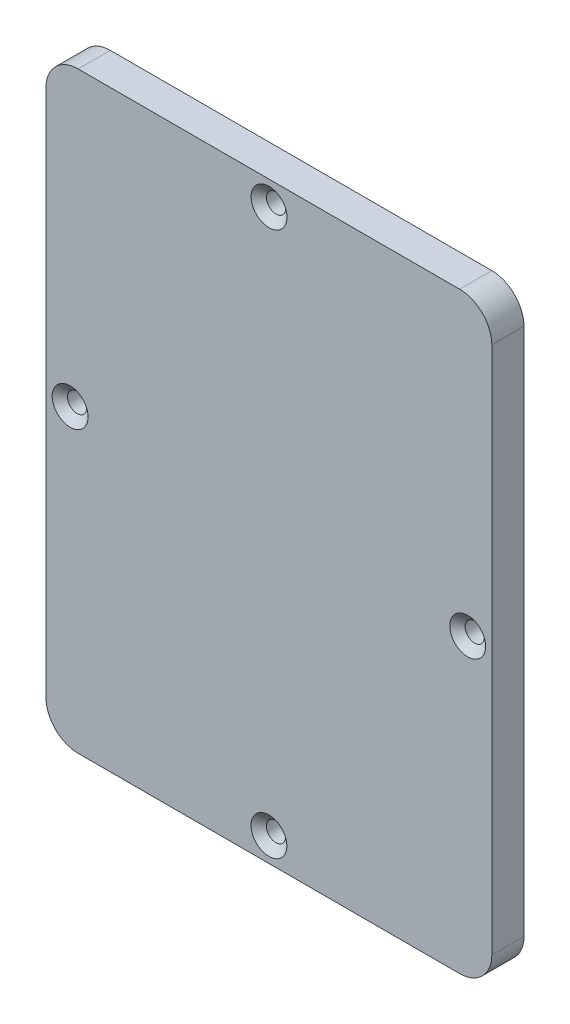
SolidWorks part; units mm, degrees
ref_plane "Front Plane" through (0, 0, 0) normal (0, 0, 1) x (1, 0, 0)
ref_plane "Top Plane" through (0, 0, 0) normal (0, 1, 0) x (1, 0, 0)
ref_plane "Right Plane" through (0, 0, 0) normal (1, 0, 0) x (0, 0, -1)
sketch "Sketch1" plane through (0, 0, 0) normal (0, 0, 1) x (1, 0, 0)
  line L4 (37.65, 117) -> (37.65, 0) construction
  line L5 (37.65, 0) -> (-6.35, 58.5) construction
  line L6 (-6.35, 58.5) -> (81.65, 58.5) construction
  line L8 (0, 0) -> (75.3, 0)
  line L9 (81.65, 6.35) -> (81.65, 110.65)
  line L10 (75.3, 117) -> (0, 117)
  line L11 (-6.35, 110.65) -> (-6.35, 6.35)
  arc A8 (-6.35, 6.35) -> (0, 0) centre (0, 6.35) ccw
  arc A9 (75.3, 0) -> (81.65, 6.35) centre (75.3, 6.35) ccw
  arc A10 (81.65, 110.65) -> (75.3, 117) centre (75.3, 110.65) ccw
  arc A11 (0, 117) -> (-6.35, 110.65) centre (0, 110.65) ccw
  circle A12 centre (37.65, 4.7625) radius 1.5875
  circle A13 centre (76.8875, 58.5) radius 1.5875
  circle A14 centre (37.6738, 112.2375) radius 1.5875
  circle A15 centre (-1.5875, 58.5) radius 1.5875
  point P16 (0, 0)
  point P26 (0, 0)
  point P27 (0, 0)
  point P28 (0, 0)
  dimension "D7" = 6.35
  dimension "D1" = 4.7625
  dimension "D2" = 4.7625
  dimension "D3" = 4.7625
  dimension "D4" = 4.7625
  dimension "D5" = 117
  dimension "D6" = 88
extrude "Boss-Extrude1" add sketch "Sketch1" along normal blind 6.35
hole_wizard "CSK for #6 Flat Head Machine Screw (100)1" positions "Sketch2" profile "Sketch3" countersink size "#6" standard "ANSI Inch" end condition through all
sketch "Sketch2" plane through (0, 0, 6.35) normal (0, 0, 1) x (1, 0, 0)
  point P0 (-1.5875, 58.5)
  point P3 (37.6738, 112.2375)
  point P6 (76.8875, 58.5)
  point P9 (37.65, 4.7625)
sketch "Sketch3" plane through (-1.5875, 58.5, 6.35) normal (1, 0, 0) x (0, -1, 0)
  line L0 (0, 0) -> (0, 6.35)
  line L1 (0, 6.35) -> (1.8986, 6.35)
  line L2 (1.8986, 6.35) -> (1.8986, 1.38)
  line L3 (1.8986, 1.38) -> (3.5433, 0)
  line L5 (3.5433, 0) -> (0, 0)
  line L6 (-1.8986, 1.38) -> (-3.5433, 0) construction
  line L11 (0, -6.35) -> (0, 107.95) construction
  dimension "Thru Hole Dia." = 3.7973
  dimension "Thru Hole Depth" = 6.35
  dimension "Near C'Sink Dia." = 7.0866
  dimension "Near C'Sink Angle" = 100
